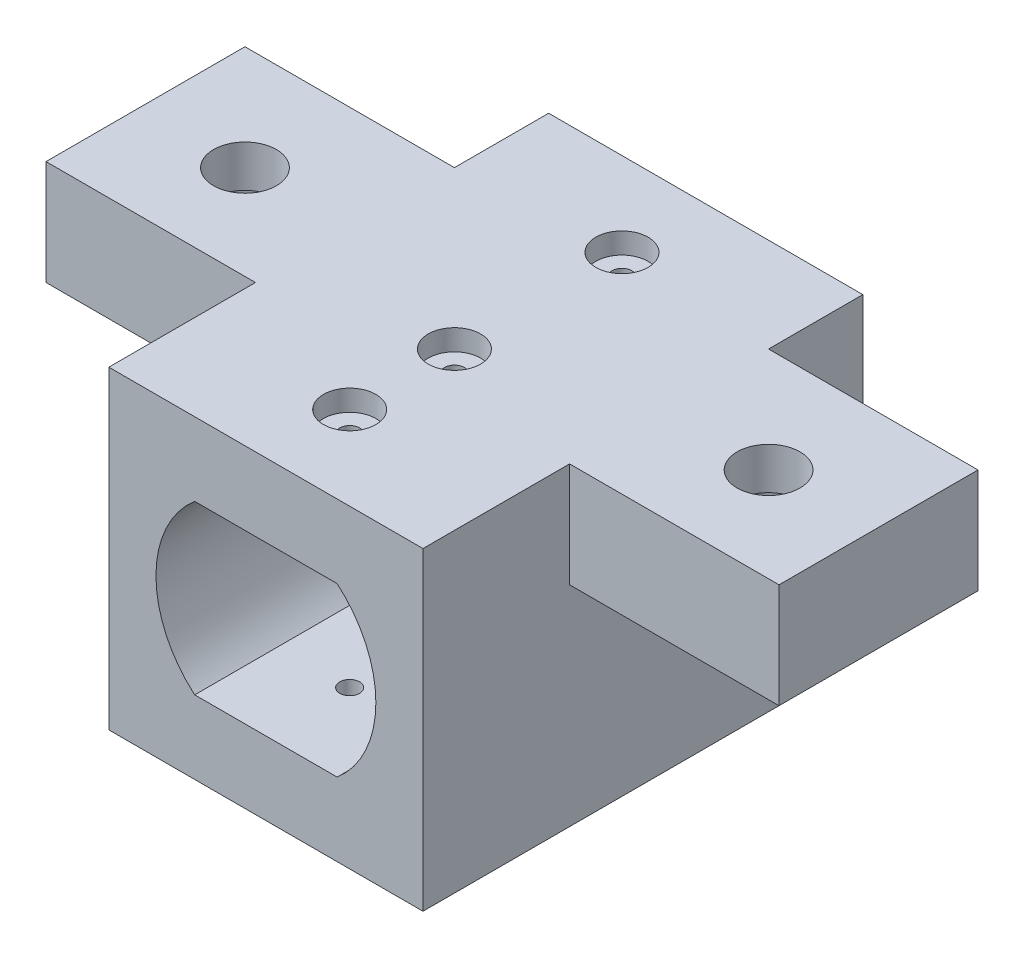
SolidWorks part; units mm, degrees
ref_plane "前视基准面" through (0, 0, 0) normal (0, 0, 1) x (1, 0, 0)
ref_plane "上视基准面" through (0, 0, 0) normal (0, 1, 0) x (1, 0, 0)
ref_plane "右视基准面" through (0, 0, 0) normal (1, 0, 0) x (0, 0, -1)
other "Configuration Table"
sketch "草图1" plane through (0, 0, 0) normal (0, 0, 1) x (1, 0, 0)
  line L1 (-15, 15) -> (15, 15)
  line L2 (-15, 15) -> (-15, -15)
  line L3 (-15, -15) -> (15, -15)
  line L4 (15, 15) -> (15, -15)
  line L5 (-15, 15) -> (15, -15) construction
  line L6 (-15, -15) -> (15, 15) construction
  circle A0 centre (0, 0) radius 10.5
  dimension "D1" = 21
  dimension "D2" = 30
  dimension "D3" = 30
extrude "凸台-拉伸1" add sketch "草图1" along normal blind 17
sketch "草图2" plane through (0, 0, 17) normal (0, 0, 1) x (1, 0, 0)
  line L0 (-6.8007, 8) -> (6.8007, 8)
  line L1 (-6.8007, -8) -> (6.8007, -8)
  line L2 (-15, -15) -> (15, -15) construction
  line L3 (-15, -15) -> (15, -15)
  line L4 (-15, -15) -> (-15, 15)
  line L5 (-15, 15) -> (15, 15)
  line L6 (15, -15) -> (15, 15)
  circle A0 centre (0, 0) radius 10.5 construction
  arc A1 (-6.8007, 8) -> (-6.8007, -8) centre (0, 0) ccw
  arc A2 (6.8007, 8) -> (6.8007, -8) centre (0, 0) cw
  point P15 (-6.8007, 8)
  dimension "D1" = 16
extrude "凸台-拉伸2" add sketch "草图2" along normal blind 25
sketch "草图3" plane through (0, 15, 0) normal (0, 1, 0) x (1, 0, 0)
  line L0 (0, -42) -> (0, 49958) construction
  line L1 (15, -42) -> (-15, -42) construction
  line L2 (15, 0) -> (-15, 0) construction
  circle A0 centre (0, -34) radius 0.95
  circle A1 centre (0, -8) radius 0.95
  circle A2 centre (0, -24) radius 0.95
  point P4 (0, -42)
  dimension "D1" = 1.9
  dimension "D2" = 1.9
  dimension "D3" = 1.9
  dimension "D4" = 8
  dimension "D5" = 10
  dimension "D6" = 8
extrude "切除-拉伸1" cut sketch "草图3" against normal through all
sketch "草图4" plane through (0, 15, 0) normal (0, 1, 0) x (1, 0, 0)
  circle A0 centre (0, -8) radius 2.5
  circle A1 centre (0, -24) radius 2.5
  circle A2 centre (0, -34) radius 2.5
  dimension "D1" = 5
  dimension "D2" = 5
  dimension "D3" = 5
extrude "切除-拉伸2" cut sketch "草图4" against normal blind 2
sketch "草图5" plane through (0, -15, 0) normal (0, -1, 0) x (1, 0, 0)
  circle A0 centre (0, 34) radius 2.5
  circle A1 centre (0, 24) radius 2.5
  circle A2 centre (0, 8) radius 2.5
  dimension "D1" = 5
  dimension "D2" = 5
  dimension "D3" = 5
extrude "切除-拉伸3" cut sketch "草图5" against normal blind 2
sketch "草图6" plane through (-15, 0, 0) normal (-1, 0, 0) x (0, 0, 1)
  line L1 (28, 15) -> (9, 15)
  line L2 (28, 15) -> (28, 5)
  line L3 (28, 5) -> (9, 5)
  line L5 (42, 15) -> (0, 15) construction
  line L6 (9, 15) -> (9, 5)
  line L7 (0, 15) -> (0, -15) construction
  dimension "D1" = 19
  dimension "D2" = 10
  dimension "D3" = 28
extrude "凸台-拉伸5" add sketch "草图6" along normal blind 20
sketch "草图8" plane through (15, 0, 0) normal (1, 0, 0) x (0, 0, -1)
  line L0 (-9, 15) -> (-9, 5)
  line L1 (-9, 15) -> (-28, 15)
  line L3 (-9, 5) -> (-28, 5)
  line L4 (-28, 15) -> (-28, 5)
  line L5 (0, -15) -> (0, 15) construction
  line L6 (-42, 15) -> (0, 15) construction
  dimension "D1" = 19
  dimension "D2" = 28
  dimension "D3" = 10
extrude "凸台-拉伸6" add sketch "草图8" along normal blind 20
sketch "草图9" plane through (0, 5, 0) normal (0, -1, 0) x (1, 0, 0)
  line L0 (-32.6753, 19) -> (49967.3247, 19) construction
  line L1 (-35, 9) -> (-15, 9) construction
  line L2 (-35, 9) -> (-35, 28) construction
  line L3 (35, 28) -> (35, 9) construction
  circle A0 centre (-25, 19) radius 3
  circle A1 centre (25, 19) radius 3
  dimension "D2" = 6
  dimension "D3" = 6
  dimension "D1" = 10
  dimension "D4" = 10
  dimension "D5" = 10
extrude "切除-拉伸4" cut sketch "草图9" against normal blind 10
sketch "草图10" plane through (0, 5, 0) normal (0, -1, 0) x (1, 0, 0)
  circle A0 centre (-25, 19) radius 4.5
  circle A1 centre (25, 19) radius 4.5
  dimension "D1" = 9
  dimension "D2" = 9
extrude "切除-拉伸5" cut sketch "草图10" against normal blind 6
